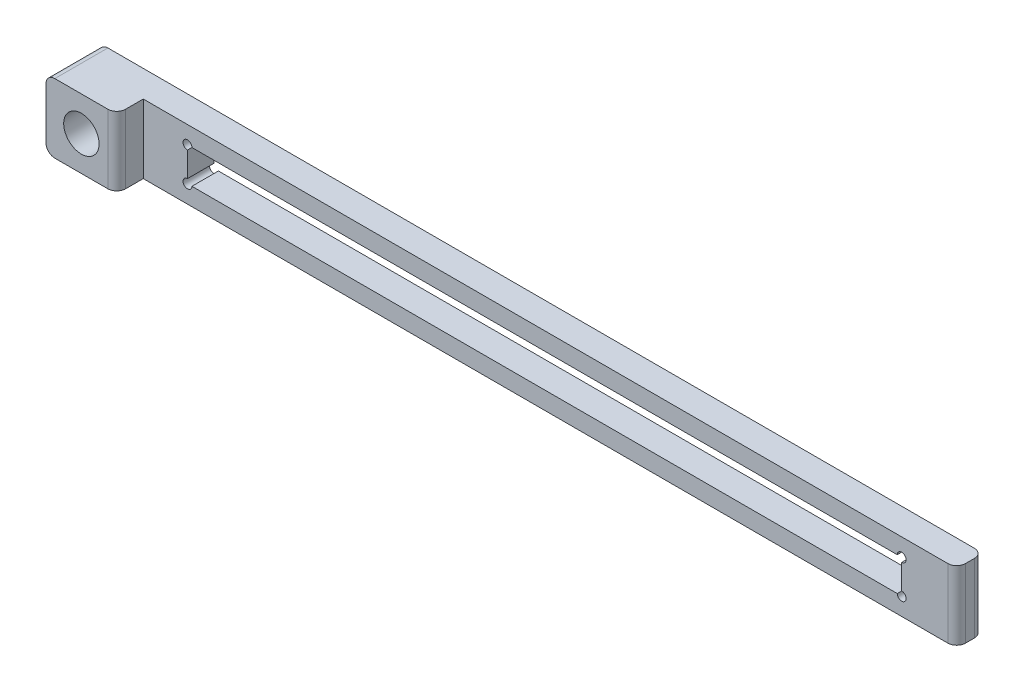
SolidWorks part; units mm, degrees
ref_plane "Ebene vorne" through (0, 0, 0) normal (0, 0, 1) x (1, 0, 0)
ref_plane "Ebene oben" through (0, 0, 0) normal (0, 1, 0) x (1, 0, 0)
ref_plane "Ebene rechts" through (0, 0, 0) normal (1, 0, 0) x (0, 0, -1)
sketch "Skizze1" plane through (0, 0, 0) normal (0, 0, 1) x (1, 0, 0)
  line L0 (-50, 0) -> (50, 0) construction
  line L1 (-50, 3.9) -> (50, 3.9)
  line L2 (-50, 3.9) -> (-50, -3.9)
  line L3 (-50, -3.9) -> (50, -3.9)
  line L4 (50, 3.9) -> (50, -3.9)
  line L5 (-50, 3.9) -> (50, -3.9) construction
  line L6 (-50, -3.9) -> (50, 3.9) construction
  line L8 (-37, 1.9) -> (43.78, 1.9)
  line L9 (-37, 1.9) -> (-37, -1.9)
  line L10 (-37, -1.9) -> (43.78, -1.9)
  line L11 (43.78, 1.9) -> (43.78, -1.9)
  point P0 (0, 0)
  dimension "D1" = 100
  dimension "D2" = 7.8
  dimension "D3" = 1.9
  dimension "D4" = 1.9
  dimension "D5" = 3.8
  dimension "D6" = 13
  dimension "D7" = 80.78
extrude "Aufsatz-Linear austragen1" add sketch "Skizze1" along normal mid plane 3
sketch "Skizze3" plane through (0, 0, 1.5) normal (0, 0, 1) x (1, 0, 0)
  line L0 (-50, -3.9) -> (50, -3.9) construction
  line L1 (-50, 3.9) -> (-42, 3.9)
  line L2 (-50, 3.9) -> (-50, -3.9)
  line L3 (-50, -3.9) -> (-42, -3.9)
  line L4 (-42, 3.9) -> (-42, -3.9)
  line L5 (-50, 3.9) -> (-42, -3.9) construction
  line L6 (-42, 3.9) -> (-50, -3.9) construction
  dimension "D1" = 8
extrude "Aufsatz-Linear austragen2" add sketch "Skizze3" along normal blind 3
sketch "Skizze5" plane through (0, 0, 4.5) normal (0, 0, 1) x (1, 0, 0)
  line L0 (-50, 3.9) -> (-42, -3.9) construction
  line L1 (-42, 3.9) -> (-50, -4.3051) construction
  line L2 (-42, 3.9) -> (-50, 3.9) construction
  line L3 (-42, -3.9) -> (-42, 3.9) construction
  line L4 (-50, 3.9) -> (-50, -3.9) construction
  circle A0 centre (-46, 0) radius 2
  dimension "D1" = 4
extrude "Schnitt-Linear austragen4" cut sketch "Skizze5" against normal through all both and the other way through all
fillet "Verrundung1" radius 1 1 edges at (-50, 3.9, 1.5)
fillet "Verrundung2" radius 1 1 edges at (-50, -3.9, 1.5)
fillet "Verrundung3" radius 1 1 edges at (-42, 0, 4.5)
fillet "Verrundung4" radius 1 1 edges at (50, 0, -1.5)
fillet "Verrundung5" radius 1 1 edges at (50, 0, 1.5)
sketch "Lochungsskizze" plane through (0, 0, 1.5) normal (0, 0, 1) x (1, 0, 0)
  circle A0 centre (-37, 1.9) radius 0.5
  circle A1 centre (-37, -1.9) radius 0.5
  circle A2 centre (43.78, -1.9) radius 0.5
  circle A3 centre (43.78, 1.9) radius 0.5
  dimension "D1" = 1
extrude "RahmenLochungen" cut sketch "Lochungsskizze" against normal through all
